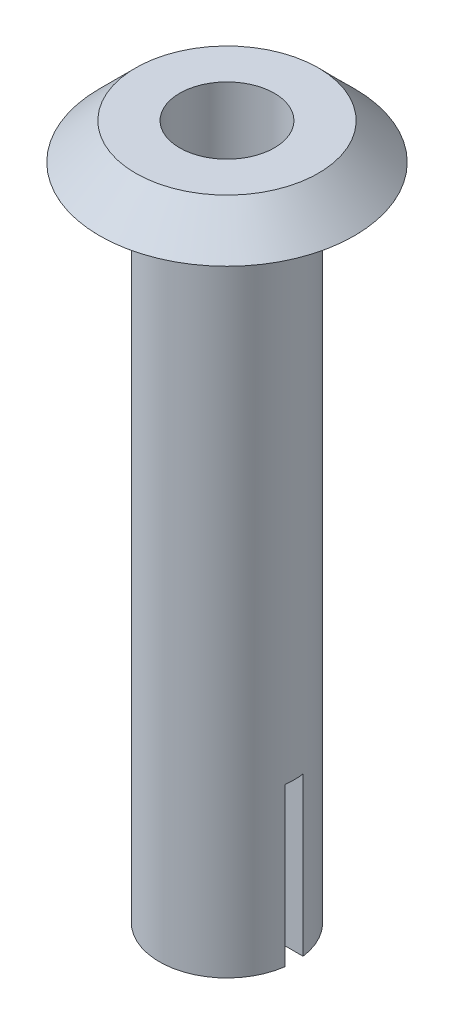
SolidWorks part; units mm, degrees
ref_plane "Alzado" through (0, 0, 0) normal (0, 0, 1) x (1, 0, 0)
ref_plane "Planta" through (0, 0, 0) normal (0, 1, 0) x (1, 0, 0)
ref_plane "Vista lateral" through (0, 0, 0) normal (1, 0, 0) x (0, 0, -1)
sketch "Croquis1" plane through (0, 0, 0) normal (0, 1, 0) x (1, 0, 0)
  circle A0 centre (0, 0) radius 1.5
extrude "Saliente-Extruir1" add sketch "Croquis1" along normal blind 15.4
sketch "Croquis2" plane through (0, 15.4, 0) normal (0, 1, 0) x (1, 0, 0)
  circle A0 centre (0, 0) radius 2.825
extrude "Saliente-Extruir2" add sketch "Croquis2" along normal blind 0.0001 and the other way blind 0.8
chamfer "Chaflán1" distance 0.8 angle 45 1 edges at (0, 15.4001, 2.825)
sketch "Croquis3" plane through (0, 15.4001, 0) normal (0, 1, 0) x (1, 0, 0)
  circle A0 centre (0, 0) radius 1.05
extrude "Cortar-Extruir1" cut sketch "Croquis3" against normal blind 13.9
fillet "Redondeo2" radius 0.8 1 edges at (0, 1.5001, 1.05)
sketch "Croquis6" plane through (0, 0, 0) normal (0, -1, 0) x (-1, 0, 0)
  line L1 (1.5, -0.2) -> (-1.5, -0.2)
  line L2 (1.5, -0.2) -> (1.5, 0.2)
  line L3 (1.5, 0.2) -> (-1.5, 0.2)
  line L4 (-1.5, -0.2) -> (-1.5, 0.2)
  line L5 (1.5, -0.2) -> (-1.5, 0.2) construction
  line L6 (1.5, 0.2) -> (-1.5, -0.2) construction
  point P0 (0, 0)
extrude "Cortar-Extruir4" cut sketch "Croquis6" against normal blind 3.5
